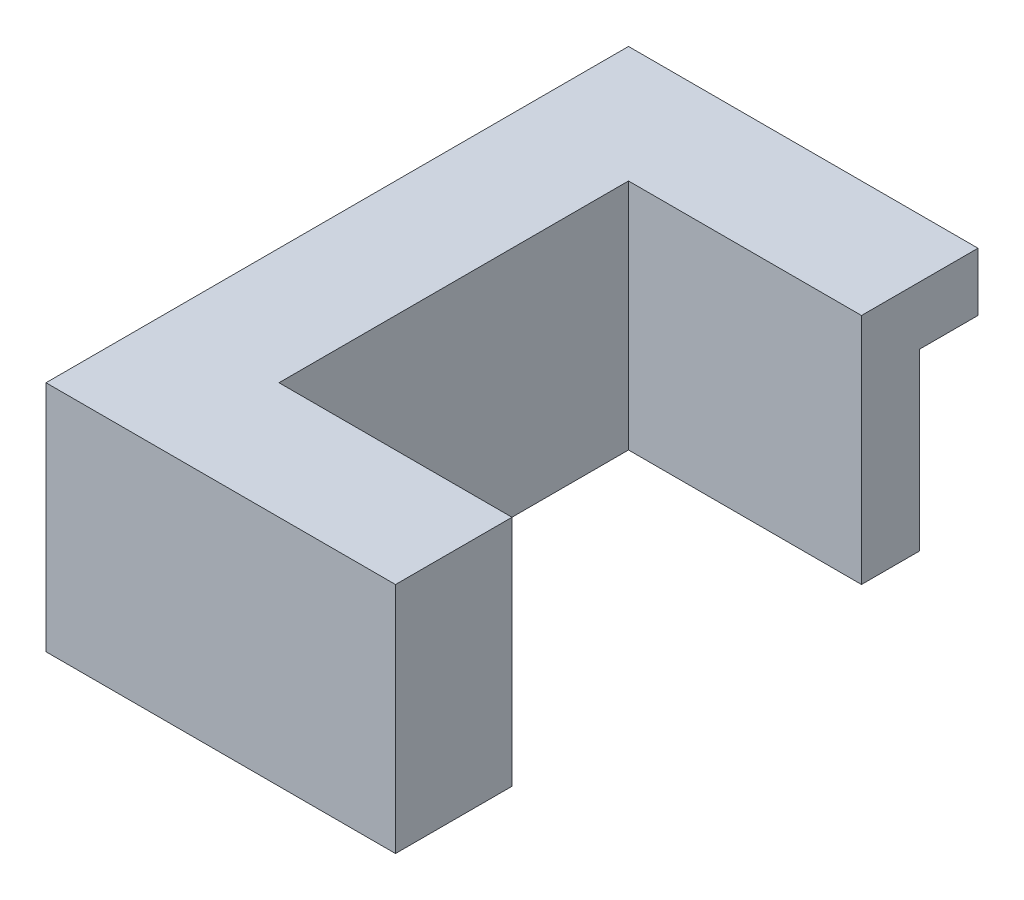
SolidWorks part; units mm, degrees
ref_plane "Přední rovina" through (0, 0, 0) normal (0, 0, 1) x (1, 0, 0)
ref_plane "Horní rovina" through (0, 0, 0) normal (0, 1, 0) x (1, 0, 0)
ref_plane "Pravá rovina" through (0, 0, 0) normal (1, 0, 0) x (0, 0, -1)
sketch "Sketch1" plane through (0, 0, 0) normal (0, 1, 0) x (1, 0, 0)
  line L0 (0, 0) -> (0, -50)
  line L1 (0, -50) -> (30, -50)
  line L2 (30, -50) -> (30, -40)
  line L3 (30, -40) -> (10, -40)
  line L4 (10, -40) -> (10, -10)
  line L5 (10, -10) -> (30, -10)
  line L6 (30, -10) -> (30, 0)
  line L7 (30, 0) -> (0, 0)
  dimension "D1" = 10
  dimension "D2" = 10
  dimension "D3" = 30
  dimension "D4" = 10
  dimension "D5" = 20
extrude "Boss-Extrude1" add sketch "Sketch1" along normal blind 20
sketch "Sketch2" plane through (30, 0, 0) normal (1, 0, 0) x (0, 0, -1)
  line L1 (0, 0) -> (-5, 0)
  line L2 (0, 0) -> (0, 15)
  line L3 (0, 15) -> (-5, 15)
  line L4 (-5, 0) -> (-5, 15)
  dimension "D1" = 5
  dimension "D2" = 15
extrude "Cut-Extrude1" cut sketch "Sketch2" against normal blind 18
equation "\"H\"= 30"
equation "\"D3@Sketch1\"=\"H\""
equation "\"L\"= 20"
equation "\"D5@Sketch1\"=\"L\""
